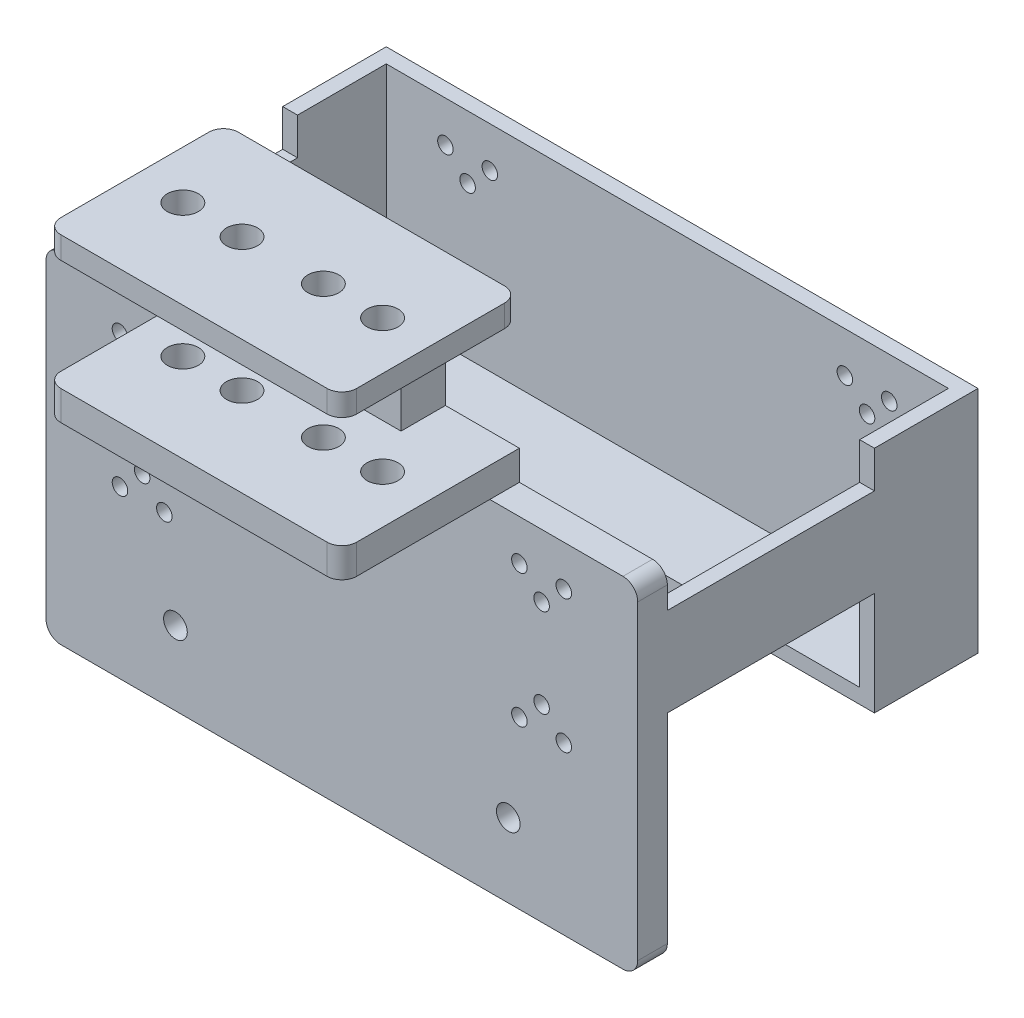
SolidWorks part; units mm, degrees
ref_plane "前视基准面" through (0, 0, 0) normal (0, 0, 1) x (1, 0, 0)
ref_plane "上视基准面" through (0, 0, 0) normal (0, 1, 0) x (1, 0, 0)
ref_plane "右视基准面" through (0, 0, 0) normal (1, 0, 0) x (0, 0, -1)
other "Configuration Table"
sketch "草图1" plane through (0, 0, 0) normal (0, 0, 1) x (1, 0, 0)
  line L1 (-40, 14.5) -> (40, 14.5)
  line L2 (-40, 14.5) -> (-40, -14.5)
  line L3 (-40, -14.5) -> (40, -14.5)
  line L4 (40, 14.5) -> (40, -14.5)
  line L5 (-40, 14.5) -> (40, -14.5) construction
  line L6 (-40, -14.5) -> (40, 14.5) construction
  point P0 (0, 0)
extrude "凸台-拉伸1" add sketch "草图1" along normal blind 2
sketch "草图4" plane through (0, 0, 2) normal (0, 0, 1) x (1, 0, 0)
  line L0 (40, -14.5) -> (40, 14.5) construction
  line L1 (40, 14.5) -> (38, 14.5)
  line L2 (40, 14.5) -> (40, -14.5)
  line L3 (40, -14.5) -> (38, -14.5)
  line L4 (38, 14.5) -> (38, -14.5)
  line L5 (40, 14.5) -> (-40, 14.5) construction
  line L6 (-40, -14.5) -> (40, -14.5) construction
  line L8 (-40, 14.5) -> (-38, 14.5)
  line L9 (-40, 14.5) -> (-40, -14.5)
  line L10 (-40, -14.5) -> (-38, -14.5)
  line L11 (-38, 14.5) -> (-38, -14.5)
  dimension "D1" = 2
  dimension "D2" = 2
extrude "凸台-拉伸2" add sketch "草图4" along normal blind 12
sketch "草图6" plane through (0, -14.5, 0) normal (0, -1, 0) x (1, 0, 0)
  line L1 (-40, 0) -> (40, 0)
  line L2 (-40, 0) -> (-40, 14)
  line L3 (-40, 14) -> (40, 14)
  line L4 (40, 0) -> (40, 14)
extrude "凸台-拉伸4" add sketch "草图6" along normal blind 2
sketch "草图7" plane through (0, 0, 14) normal (0, 0, 1) x (1, 0, 0)
  line L0 (-40, 14.5) -> (-40, -16.5) construction
  line L1 (-40, 9.5) -> (-38, 9.5)
  line L2 (-40, 9.5) -> (-40, -2.5)
  line L3 (-40, -2.5) -> (-38, -2.5)
  line L4 (-38, 9.5) -> (-38, -2.5)
  line L5 (-38, -14.5) -> (-38, 14.5) construction
  line L6 (-38, 14.5) -> (-40, 14.5) construction
  line L7 (38, 14.5) -> (38, -14.5) construction
  line L8 (38, 9.5) -> (40, 9.5)
  line L9 (38, 9.5) -> (38, -2.5)
  line L10 (38, -2.5) -> (40, -2.5)
  line L11 (40, 9.5) -> (40, -2.5)
  line L12 (40, -16.5) -> (40, 14.5) construction
  dimension "D1" = 5
  dimension "D2" = 12
extrude "凸台-拉伸5" add sketch "草图7" along normal blind 28
sketch "草图8" plane through (0, 0, 42) normal (0, 0, 1) x (1, 0, 0)
  line L1 (-40, 14.5) -> (40, 14.5)
  line L2 (-40, 14.5) -> (-40, -16.5)
  line L3 (-40, -16.5) -> (40, -16.5)
  line L4 (40, 14.5) -> (40, -16.5)
extrude "凸台-拉伸6" add sketch "草图8" along normal blind 4
sketch "草图2" plane through (0, 0, 2) normal (0, 0, 1) x (1, 0, 0)
  line L0 (0, 0) -> (27, 0) construction
  line L2 (0, 0) -> (0, 13.1686) construction
  circle A0 centre (-30, 9) radius 1.05
  circle A2 centre (-24, 9) radius 1.05
  circle A3 centre (-27, 6) radius 1.05
  circle A4 centre (-27, -6) radius 1.05
  circle A5 centre (-24, -9) radius 1.05
  circle A7 centre (-30, -9) radius 1.05
  circle A8 centre (27, -6) radius 1.05
  circle A9 centre (30, -9) radius 1.05
  circle A10 centre (24, -9) radius 1.05
  circle A12 centre (27, 6) radius 1.05
  circle A13 centre (30, 9) radius 1.05
  circle A14 centre (24, 9) radius 1.05
  point P3 (27, 6)
  point P5 (27, 9)
  point P6 (30, 9)
  point P7 (24, 9)
  point P8 (24, -9)
  point P9 (27, -6)
  point P10 (27, -9)
  point P11 (30, -9)
  point P14 (-30, -9)
  point P15 (-27, -9)
  point P16 (-27, -6)
  point P17 (-24, -9)
  point P18 (-24, 9)
  point P19 (-30, 9)
  point P20 (-27, 9)
  point P21 (-27, 6)
  dimension "D2" = 27
  dimension "D3" = 6
  dimension "D4" = 3
  dimension "D5" = 3
  dimension "D6" = 3
extrude "切除-拉伸1" cut sketch "草图2" against normal through all and the other way up to surface other way up to face at (0, -1, 46)
sketch "草图12" plane through (0, 14.5, 0) normal (0, 1, 0) x (1, 0, 0)
  line L0 (40, -42) -> (-40, -42) construction
  line L1 (-20, -42) -> (20, -42)
  line L2 (-20, -42) -> (-20, -66)
  line L3 (-20, -66) -> (20, -66)
  line L4 (20, -42) -> (20, -66)
  dimension "D1" = 24
  dimension "D2" = 20
  dimension "D3" = 20
extrude "凸台-拉伸9" add sketch "草图12" along normal blind 4
sketch "草图13" plane through (0, 18.5, 0) normal (0, 1, 0) x (1, 0, 0)
  line L0 (-20, -54) -> (20, -54) construction
  line L1 (-20, -42) -> (-20, -66) construction
  line L2 (20, -66) -> (20, -42) construction
  circle A0 centre (-13.5, -54) radius 2.1
  circle A1 centre (-5.5, -54) radius 2.1
  circle A2 centre (5.5, -54) radius 2.1
  circle A3 centre (13.5, -54) radius 2.1
  point P6 (-5.5, -54)
  point P7 (-13.5, -54)
  point P8 (5.5, -54)
  point P9 (13.5, -54)
  point P10 (0, -54)
  dimension "D1" = 5.5
  dimension "D2" = 5.5
  dimension "D3" = 8
  dimension "D4" = 8
extrude "切除-拉伸3" cut sketch "草图13" against normal up to next and the other way through all
sketch "草图14" plane through (0, 18.5, 0) normal (0, 1, 0) x (1, 0, 0)
  line L0 (-20, -45) -> (20, -45) construction
  line L1 (-20, -42) -> (-20, -66) construction
  line L2 (20, -66) -> (20, -42) construction
  line L3 (20, -42) -> (-20, -42) construction
  line L4 (-10, -48) -> (10, -48)
  line L5 (-10, -48) -> (-10, -42)
  line L6 (-10, -42) -> (10, -42)
  line L7 (10, -48) -> (10, -42)
  line L8 (-10, -48) -> (10, -42) construction
  line L9 (-10, -42) -> (10, -48) construction
  point P0 (-5.5, -54)
  point P8 (0, -45)
  point P15 (0, 0)
  dimension "D1" = 9
  dimension "D2" = 20
extrude "凸台-拉伸10" add sketch "草图14" along normal blind 15
sketch "草图15" plane through (0, 33.5, 0) normal (0, 1, 0) x (1, 0, 0)
  line L0 (10, -42) -> (-10, -42) construction
  line L1 (-20, -42) -> (20, -42)
  line L2 (-20, -42) -> (-20, -66)
  line L3 (-20, -66) -> (20, -66)
  line L4 (20, -42) -> (20, -66)
  point P7 (0, -42)
  point P8 (0, -42)
  dimension "D1" = 40
extrude "凸台-拉伸11" add sketch "草图15" along normal blind 3
sketch "草图16" plane through (0, 36.5, 0) normal (0, 1, 0) x (1, 0, 0)
  line L0 (-20, -54) -> (20, -54) construction
  line L1 (-20, -42) -> (-20, -66) construction
  line L2 (20, -66) -> (20, -42) construction
  circle A0 centre (-13.5, -54) radius 2.1
  circle A1 centre (-5.5, -54) radius 2.1
  circle A2 centre (5.5, -54) radius 2.1
  circle A3 centre (13.5, -54) radius 2.1
  point P6 (-5.5, -54)
  point P7 (-13.5, -54)
  point P8 (5.5, -54)
  point P9 (13.5, -54)
  point P11 (0, -54)
  dimension "D1" = 8
  dimension "D2" = 5.5
  dimension "D3" = 5.5
  dimension "D4" = 8
extrude "切除-拉伸4" cut sketch "草图16" against normal blind 3
sketch "草图21" plane through (0, 0, 46) normal (0, 0, 1) x (1, 0, 0)
  line L0 (0, -16.5) -> (0, 0) construction
  line L1 (-40, 14.5) -> (-40, -16.5) construction
  line L2 (0, -16.5) -> (40, -16.5)
  line L3 (-40, -16.5) -> (40, -16.5) construction
  line L4 (40, -16.5) -> (40, -31.5)
  line L5 (40, -31.5) -> (-40, -31.5)
  line L6 (-40, -31.5) -> (-40, -16.5)
  line L7 (-40, -16.5) -> (0, -16.5)
  line L8 (40, -16.5) -> (40, 14.5) construction
  dimension "D3" = 15
extrude "凸台-拉伸14" add sketch "草图21" against normal up to surface (4 mm away) up to face at (31.05, -9, 42)
sketch "草图22" plane through (0, 0, 46) normal (0, 0, 1) x (1, 0, 0)
  line L0 (-40, -21.5) -> (40, -21.5) construction
  line L4 (-40, -31.5) -> (40, -31.5) construction
  circle A0 centre (-22.5, -21.5) radius 1.6
  circle A1 centre (22.5, -21.5) radius 1.6
  point P6 (22.5, -21.5)
  point P7 (-22.5, -21.5)
  point P8 (0, -21.5)
  dimension "D3" = 10
  dimension "D1" = 22.5
  dimension "D2" = 22.5
extrude "切除-拉伸5" cut sketch "草图22" against normal up to surface (4 mm away)
fillet "圆角1" radius 2 10 edges at (-20, 35, 42) (20, 35, 42) (20, 35, 66) (20, 16.5, 66) (-20, 35, 66) (-20, 16.5, 66) (40, 14.5, 44) (-40, 14.5, 44) (-40, -31.5, 44) (40, -31.5, 44)
